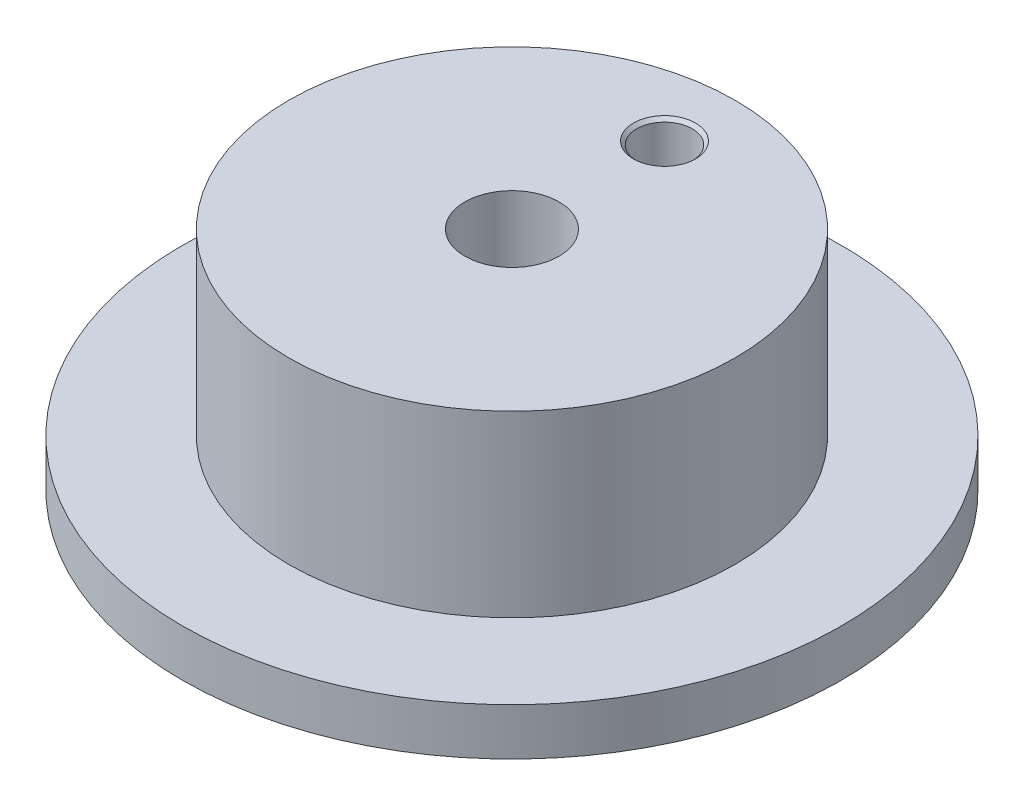
SolidWorks part; units mm, degrees
material "1023 Carbon Steel Sheet (SS)"
ref_plane "Front Plane" through (0, 0, 0) normal (0, 0, 1) x (1, 0, 0)
ref_plane "Top Plane" through (0, 0, 0) normal (0, 1, 0) x (1, 0, 0)
ref_plane "Right Plane" through (0, 0, 0) normal (1, 0, 0) x (0, 0, -1)
sketch "Sketch1" plane through (0, 0, 0) normal (0, 0, 1) x (1, 0, 0)
  line L0 (0, 0) -> (-10, 0) construction
  line L1 (-10, 0) -> (-10, -48)
  line L2 (-10, -48) -> (-12.5, -48)
  line L3 (-12.5, -48) -> (-12.5, -46.2)
  line L4 (-12.7, -46) -> (-15.542, -46)
  line L5 (-15.75, -46.208) -> (-15.75, -48)
  line L6 (-15.75, -48) -> (-18.5, -48)
  line L7 (-18.5, -48) -> (-18.5, -46.208)
  line L8 (-18.708, -46) -> (-21.542, -46)
  line L9 (-21.75, -46.208) -> (-21.75, -48)
  line L10 (-21.75, -48) -> (-24, -48)
  line L11 (-24, -48) -> (-24, -20)
  line L13 (-39.4, -20) -> (-39.4, -48)
  line L14 (-39.4, -48) -> (-42, -48)
  line L15 (-42, -48) -> (-42, -46.208)
  line L16 (-42.208, -46) -> (-45.042, -46)
  line L17 (-45.25, -46.208) -> (-45.25, -48)
  line L18 (-45.25, -48) -> (-47.75, -48)
  line L19 (-47.75, -48) -> (-47.75, -46.208)
  line L20 (-47.958, -46) -> (-50.792, -46)
  line L21 (-51, -46.208) -> (-51, -48)
  line L22 (-51, -48) -> (-70, -48)
  line L23 (-70, -48) -> (-70, -38)
  line L24 (-70, -38) -> (-47.4, -38)
  line L25 (-47.4, -38) -> (-47.4, 0)
  line L26 (-47.4, 0) -> (-10, 0)
  line L28 (-39.4, -20) -> (-24, -20)
  line L29 (0, 0) -> (0, -83.2336) construction
  arc A0 (-12.5, -46.2) -> (-12.7, -46) centre (-12.7, -46.2) ccw
  arc A1 (-15.542, -46) -> (-15.75, -46.208) centre (-15.542, -46.208) ccw
  arc A2 (-21.542, -46) -> (-21.75, -46.208) centre (-21.542, -46.208) ccw
  arc A3 (-18.5, -46.208) -> (-18.708, -46) centre (-18.708, -46.208) ccw
  arc A4 (-50.792, -46) -> (-51, -46.208) centre (-50.792, -46.208) ccw
  arc A5 (-47.75, -46.208) -> (-47.958, -46) centre (-47.958, -46.208) ccw
  arc A6 (-45.042, -46) -> (-45.25, -46.208) centre (-45.042, -46.208) ccw
  arc A7 (-42, -46.208) -> (-42.208, -46) centre (-42.208, -46.208) ccw
  point P30 (-12.5, -46)
  point P33 (-15.75, -46)
  point P36 (-21.75, -46)
  point P39 (-18.5, -46)
  point P42 (-51, -46)
  point P45 (-47.75, -46)
  point P48 (-45.25, -46)
  point P51 (-42, -46)
  dimension "D26" = 0.2
  dimension "D27" = 0.208
  dimension "D28" = 0.208
  dimension "D29" = 0.208
  dimension "D1" = 10
  dimension "D2" = 48
  dimension "D3" = 2.5
  dimension "D4" = 2
  dimension "D5" = 3.25
  dimension "D6" = 2
  dimension "D7" = 2.75
  dimension "D8" = 2
  dimension "D9" = 3.25
  dimension "D10" = 2
  dimension "D11" = 2.25
  dimension "D12" = 28
  dimension "D13" = 15.4
  dimension "D14" = 28
  dimension "D15" = 38
  dimension "D16" = 22.6
  dimension "D17" = 10
  dimension "D18" = 2.6
  dimension "D19" = 2
  dimension "D20" = 3.25
  dimension "D21" = 2.5
  dimension "D22" = 2
  dimension "D23" = 2
  dimension "D24" = 3.25
  dimension "D25" = 37.4
revolve "Revolve1" add sketch "Sketch1" angle 360 about L29
sketch "Sketch2" plane through (0, 0, 0) normal (0, 1, 0) x (1, 0, 0)
  point P0 (0, 32.4)
  dimension "D1" = 32.4
hole_wizard "G1/4 Tapped Hole1" positions "Sketch3" profile "Sketch4" tap size "G1/4" standard "BSI" end condition up to next
sketch "Sketch3" plane through (0, 0, 0) normal (0, 1, 0) x (1, 0, 0)
  point P0 (0, 32.4)
sketch "Sketch4" plane through (0, 0, -32.4) normal (1, 0, 0) x (0, 0, 1)
  line L0 (0, 0) -> (0, 20)
  line L1 (0, 20) -> (5.9, 20)
  line L2 (5.9, 20) -> (5.9, 0.7035)
  line L3 (5.9, 0.7035) -> (6.6035, 0)
  line L5 (6.6035, 0) -> (0, 0)
  line L6 (-5.9, 0.7035) -> (-6.6035, 0) construction
  line L11 (0, -6.35) -> (0, 107.95) construction
  dimension "Thru Tap Drill Dia." = 11.8
  dimension "Thru Tap Drill Depth" = 20
  dimension "Near C'Sink Dia." = 13.207
  dimension "Near C'Sink Angle" = 90
cosmetic thread "Hole Thread1" parameters "D2"=13.157
